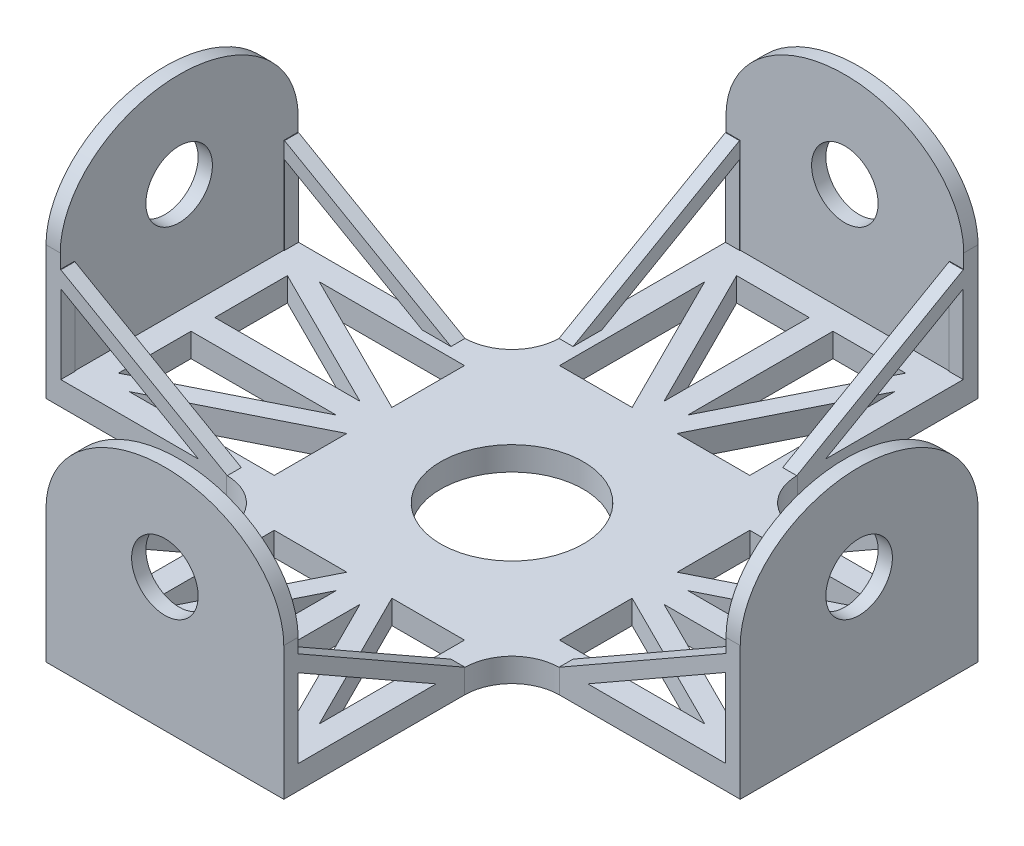
SolidWorks part; units mm, degrees
ref_plane "Front Plane" through (0, 0, 0) normal (0, 0, 1) x (1, 0, 0)
ref_plane "Top Plane" through (0, 0, 0) normal (0, 1, 0) x (1, 0, 0)
ref_plane "Right Plane" through (0, 0, 0) normal (1, 0, 0) x (0, 0, -1)
sketch "Sketch2" plane through (0, 0, 0) normal (0, 1, 0) x (1, 0, 0)
  line L0 (-25, 0) -> (25, 0)
  line L1 (-73, -73) -> (73, -73)
  line L2 (-73, -73) -> (-73, 73)
  line L3 (-73, 73) -> (73, 73)
  line L4 (73, -73) -> (73, 73)
  line L5 (-73, -73) -> (73, 73) construction
  line L6 (-73, 73) -> (73, -73) construction
  line L7 (25, 0) -> (0, 0)
  line L8 (0, 0) -> (0, 25)
  line L9 (-25, -73) -> (-25, 73)
  line L10 (25, -73) -> (25, 73)
  line L11 (73, -25) -> (-73, -25)
  line L12 (73, 25) -> (-73, 25)
  line L13 (20, 30) -> (20, 48.0837)
  line L15 (-65, 2.5) -> (-65, 17.7639)
  line L16 (-65, 2.5) -> (-34.4721, 2.5)
  line L18 (-48.0837, -20) -> (-60.5279, -20)
  line L19 (-65, -17.7639) -> (-65, -2.5)
  line L20 (-60.5279, 20) -> (-30, 20)
  line L21 (-30, 20) -> (-30, 4.7361)
  line L22 (-30, -20) -> (-48.0837, -20)
  line L23 (-34.4721, -2.5) -> (-65, -2.5)
  line L24 (-60.5279, -20) -> (-30, -4.7361)
  line L25 (-60.5279, 20) -> (-30, 4.7361)
  line L26 (-65, 17.7639) -> (-34.4721, 2.5)
  line L27 (-65, -17.7639) -> (-34.4721, -2.5)
  line L28 (-30, -4.7361) -> (-30, -20)
  line L29 (-65, 2.5) -> (-65, 17.7639)
  line L30 (4.7361, 30) -> (20, 30)
  line L31 (20, 60.5279) -> (4.7361, 30)
  line L32 (20, 48.0837) -> (20, 60.5279)
  line L33 (17.7639, 65) -> (2.5, 34.4721)
  line L34 (2.5, 34.4721) -> (2.5, 65)
  line L35 (17.7639, 65) -> (2.5, 65)
  line L36 (-20, 60.5279) -> (-4.7361, 30)
  line L37 (-20, 30) -> (-4.7361, 30)
  line L38 (-20, 60.5279) -> (-20, 30)
  line L39 (-2.5, 65) -> (-17.7639, 65)
  line L40 (-2.5, 65) -> (-2.5, 34.4721)
  line L41 (-17.7639, 65) -> (-2.5, 34.4721)
  line L42 (30, 4.7361) -> (30, 20)
  line L43 (60.5279, 20) -> (30, 4.7361)
  line L44 (48.0837, 20) -> (60.5279, 20)
  line L45 (30, 20) -> (48.0837, 20)
  line L46 (65, 17.7639) -> (65, 2.5)
  line L47 (34.4721, 2.5) -> (65, 2.5)
  line L48 (65, 17.7639) -> (34.4721, 2.5)
  line L49 (65, -2.5) -> (34.4721, -2.5)
  line L50 (65, -17.7639) -> (34.4721, -2.5)
  line L51 (65, -2.5) -> (65, -17.7639)
  line L52 (60.5279, -20) -> (30, -20)
  line L53 (30, -20) -> (30, -4.7361)
  line L54 (60.5279, -20) -> (30, -4.7361)
  line L55 (-20, -30) -> (-20, -48.0837)
  line L56 (-4.7361, -30) -> (-20, -30)
  line L57 (-20, -60.5279) -> (-4.7361, -30)
  line L58 (-20, -48.0837) -> (-20, -60.5279)
  line L59 (-17.7639, -65) -> (-2.5, -34.4721)
  line L60 (-2.5, -34.4721) -> (-2.5, -65)
  line L61 (-17.7639, -65) -> (-2.5, -65)
  line L62 (2.5, -65) -> (17.7639, -65)
  line L63 (2.5, -65) -> (2.5, -34.4721)
  line L64 (17.7639, -65) -> (2.5, -34.4721)
  line L65 (20, -60.5279) -> (4.7361, -30)
  line L66 (20, -30) -> (4.7361, -30)
  line L67 (20, -60.5279) -> (20, -30)
  circle A0 centre (0, 0) radius 15
  point P0 (0, 0)
  point P9 (0, 0)
  point P13 (-25, 0)
  point P17 (25, 0)
  point P27 (-65, 0)
  dimension "D1" = 146
  dimension "D2" = 146
  dimension "D4" = 5
  dimension "D5" = 5
  dimension "D6" = 5
  dimension "D7" = 5
  dimension "D8" = 4
extrude "Boss-Extrude2" add sketch "Sketch2" along normal blind 5 contours L12 L10 L3 L9 L41 L39 L40 L38 L36 L37 L35 L33 L34 L32 L13 L30 L31 | L4 L12 L10 L11 L54 L52 L53 L48 L46 L47 L42 L45 L44 L43 L49 L51 L50 | L10 L11 L9 L1 L67 L65 L66 L64 L62 L63 L61 L59 L60 L58 L55 L56 L57 | L9 L12 L2 L11 L27 L19 L23 L25 L20 L21 L15 L26 L16 L24 L28 L22 L18 | A0 L0 L9 L11 L10 L7 | A0 L7 L10 L12 L8 | A0 L8 L12 L9 L0
sketch "Sketch3" plane through (0, 5, 0) normal (0, 1, 0) x (1, 0, 0)
  line L0 (-25, -25) -> (-73, -25) construction
  line L1 (-73, 25) -> (-70, 25)
  line L2 (-73, 25) -> (-73, -25)
  line L3 (-73, -25) -> (-70, -25)
  line L4 (-70, 25) -> (-70, -25)
  line L5 (25, 25) -> (25, 73) construction
  line L6 (-25, 73) -> (25, 73)
  line L7 (-25, 73) -> (-25, 70)
  line L8 (-25, 70) -> (25, 70)
  line L9 (25, 73) -> (25, 70)
  line L10 (73, -25) -> (25, -25) construction
  line L11 (73, 25) -> (70, 25)
  line L12 (73, 25) -> (73, -25)
  line L13 (73, -25) -> (70, -25)
  line L14 (70, 25) -> (70, -25)
  line L15 (25, -73) -> (25, -25) construction
  line L16 (-25, -73) -> (25, -73)
  line L17 (-25, -73) -> (-25, -70)
  line L18 (-25, -70) -> (25, -70)
  line L19 (25, -73) -> (25, -70)
extrude "Boss-Extrude3" add sketch "Sketch3" along normal blind 50
sketch "Sketch4" plane through (70, 0, 0) normal (-1, 0, 0) x (0, 0, 1)
  line L0 (0, 5) -> (0, 28)
  line L1 (-25, 5) -> (25, 5) construction
  line L2 (-25, 55) -> (-25, 5) construction
  line L3 (-25, 28) -> (-25, 55)
  line L4 (-25, 55) -> (25, 55)
  line L5 (25, 55) -> (25, 28)
  circle A0 centre (0, 28) radius 7
  ellipse E0 centre (0, 28) end of major axis (-25, 28) minor radius 20
  dimension "D1" = 14
  dimension "D2" = 20
  dimension "D3" = 23
extrude "Cut-Extrude2" cut sketch "Sketch4" along normal blind 160 and the other way blind 160
sketch "Sketch7" plane through (0, 0, 70) normal (0, 0, -1) x (-1, 0, 0)
  line L0 (0, 5) -> (0, 28)
  line L1 (-25, 5) -> (25, 5) construction
  line L2 (0, 28) -> (0, 48)
  line L3 (-25, 55) -> (-25, 5) construction
  circle A0 centre (0, 28) radius 7
  ellipse E0 centre (0, 28) end of major axis (-25, 28) minor radius 20
  line M4 (25, 5) -> (25, 55)
  line M5 (25, 55) -> (-25, 55)
  line M6 (-25, 55) -> (-25, 5)
  dimension "D1" = 23
  dimension "D2" = 20
extrude "Cut-Extrude3" cut sketch "Sketch7" against normal blind 160 and the other way blind 160 contours E0 M4 M5 M6 | L2 A0 L0 | L0 A0 L2
fillet "Fillet1" radius 10 4 edges at (-25, 2.5, -25) (-25, 2.5, 25) (25, 2.5, 25) (25, 2.5, -25)
sketch "Sketch8" plane through (0, 5, 0) normal (0, 1, 0) x (1, 0, 0)
  line L0 (-15, 0) -> (-27.941, 0)
  line L1 (-70, -25) -> (-34.8866, -25)
  line L2 (-70, -25) -> (-70, -22.0443)
  line L3 (-70, -22.0443) -> (-34.8866, -22.0443)
  line L4 (-34.8866, -25) -> (-34.8866, -22.0443)
  line L5 (-27.941, 0) -> (-15, 0)
  line L6 (-15, 0) -> (-15, -15)
  line L7 (-70, 22.0443) -> (-34.8866, 22.0443)
  line L8 (-34.8866, 25) -> (-34.8866, 22.0443)
  line L9 (-70, 25) -> (-34.8866, 25)
  line L10 (-70, 25) -> (-70, 22.0443)
  line L11 (0, -15) -> (0, -28.9412)
  line L12 (70, 25) -> (70, 22.0443)
  line L13 (70, 25) -> (34.8866, 25)
  line L14 (34.8866, 25) -> (34.8866, 22.0443)
  line L15 (70, 22.0443) -> (34.8866, 22.0443)
  line L16 (70, -22.0443) -> (34.8866, -22.0443)
  line L17 (34.8866, -25) -> (34.8866, -22.0443)
  line L18 (70, -25) -> (34.8866, -25)
  line L19 (70, -25) -> (70, -22.0443)
  line L20 (0, 0) -> (15, -15)
  line L21 (-25, 70) -> (-22.0443, 70)
  line L22 (-25, 70) -> (-25, 34.8866)
  line L23 (-25, 34.8866) -> (-22.0443, 34.8866)
  line L24 (-22.0443, 70) -> (-22.0443, 34.8866)
  line L25 (-25, -70) -> (-25, -34.8866)
  line L26 (-25, -34.8866) -> (-22.0443, -34.8866)
  line L27 (-22.0443, -70) -> (-22.0443, -34.8866)
  line L28 (-25, -70) -> (-22.0443, -70)
  line L29 (25, -70) -> (22.0443, -70)
  line L30 (25, -70) -> (25, -34.8866)
  line L31 (25, -34.8866) -> (22.0443, -34.8866)
  line L32 (22.0443, -70) -> (22.0443, -34.8866)
  line L33 (22.0443, 70) -> (22.0443, 34.8866)
  line L34 (25, 34.8866) -> (22.0443, 34.8866)
  line L35 (25, 70) -> (25, 34.8866)
  line L36 (25, 70) -> (22.0443, 70)
  circle A0 centre (0, 0) radius 15 construction
extrude "Boss-Extrude4" add sketch "Sketch8" along normal blind 20 contours L18 L19 L16 L17 | L35 L36 L33 L34 | L24 L21 L22 L23 | L9 L10 L7 L8 | L1 L4 L3 L2 | L32 L29 L30 L31 | L13 L14 L15 L12 | L25 L26 L27 L28
sketch "Sketch9" plane through (0, 0, -25) normal (0, 0, -1) x (-1, 0, 0)
  line L0 (-69.8866, 25) -> (-34.8866, 5)
  line L1 (-34.8866, 25) -> (-69.8866, 25)
  line L2 (-34.8866, 25) -> (-34.8866, 5)
  line L3 (-34.8866, 5) -> (-69.8866, 5)
  line L4 (-69.8866, 25) -> (-69.8866, 5)
  line L5 (-52.3866, 15) -> (-53.875, 12.3953)
  line L6 (-53.875, 12.3953) -> (-40.9333, 5)
  line L7 (-40.9333, 5) -> (-69.8866, 21.5447)
  line L8 (-69.8866, 21.5447) -> (-69.8866, 5)
  line L9 (-40.9333, 5) -> (-69.8866, 21.5447)
  line M10 (-34.8866, 5) -> (-34.8866, 25)
  line M11 (-34.8866, 25) -> (-70, 25)
  dimension "D1" = 3
extrude "Cut-Extrude5" cut sketch "Sketch9" against normal blind 100 contours L0 M11 M10 | L6 L7 L4 L3
sketch "Sketch10" plane through (25, 0, 0) normal (1, 0, 0) x (0, 0, -1)
  line L0 (69.8866, 25) -> (34.8866, 5)
  line L1 (34.8866, 25) -> (69.8866, 25)
  line L2 (34.8866, 25) -> (34.8866, 5)
  line L3 (34.8866, 5) -> (69.8866, 5)
  line L4 (69.8866, 25) -> (69.8866, 5)
  line L5 (52.3866, 15) -> (53.875, 12.3953)
  line L6 (53.875, 12.3953) -> (69.8866, 21.5447)
  line L7 (69.8866, 21.5447) -> (40.9333, 5)
  line L8 (69.8866, 21.5447) -> (69.8866, 5)
  line L9 (40.9333, 5) -> (69.8866, 21.5447)
  line M8 (70, 25) -> (34.8866, 25)
  line M9 (34.8866, 25) -> (34.8866, 5)
extrude "Cut-Extrude6" cut sketch "Sketch10" against normal blind 100 contours L6 L7 L3 L4 | L0 M8 M9
sketch "Sketch12" plane through (-25, 0, 0) normal (-1, 0, 0) x (0, 0, 1)
  line L0 (70, 25) -> (34.8866, 5)
  line L1 (70, 25) -> (34.8866, 25)
  line L2 (70, 25) -> (70, 5)
  line L3 (70, 5) -> (34.8866, 5)
  line L4 (34.8866, 25) -> (34.8866, 5)
  line L5 (52.4433, 15) -> (53.9281, 12.3932)
  line L6 (53.9281, 12.3932) -> (70, 21.5475)
  line L7 (70, 21.5475) -> (40.948, 5)
  line L8 (40.948, 5) -> (70, 5)
  line L9 (70, 21.5475) -> (70, 5)
  line M2 (70, 25) -> (34.8866, 25)
  line M3 (34.8866, 25) -> (34.8866, 5)
  dimension "D1" = 20
  dimension "D2" = 3
extrude "Cut-Extrude8" cut sketch "Sketch12" against normal blind 100 contours L6 L7 L3 L2 | L0 M2 M3
sketch "Sketch14" plane through (0, 0, 25) normal (0, 0, 1) x (1, 0, 0)
  line L0 (-69.8866, 25) -> (-34.8866, 5)
  line L1 (-34.8866, 25) -> (-69.8866, 25)
  line L2 (-34.8866, 25) -> (-34.8866, 5)
  line L3 (-34.8866, 5) -> (-69.8866, 5)
  line L4 (-69.8866, 25) -> (-69.8866, 5)
  line L5 (-52.3866, 15) -> (-53.875, 12.3953)
  line L6 (-53.875, 12.3953) -> (-40.9333, 5)
  line L7 (-40.9333, 5) -> (-69.8866, 21.5447)
  line L8 (-69.8866, 21.5447) -> (-69.8866, 5)
  line L9 (-40.9333, 5) -> (-69.8866, 5)
  line M8 (-34.8866, 5) -> (-34.8866, 25)
  line M9 (-34.8866, 25) -> (-70, 25)
  dimension "D1" = 20
extrude "Cut-Extrude10" cut sketch "Sketch14" against normal blind 100 contours L6 L7 L4 L3 | L0 M9 M8
